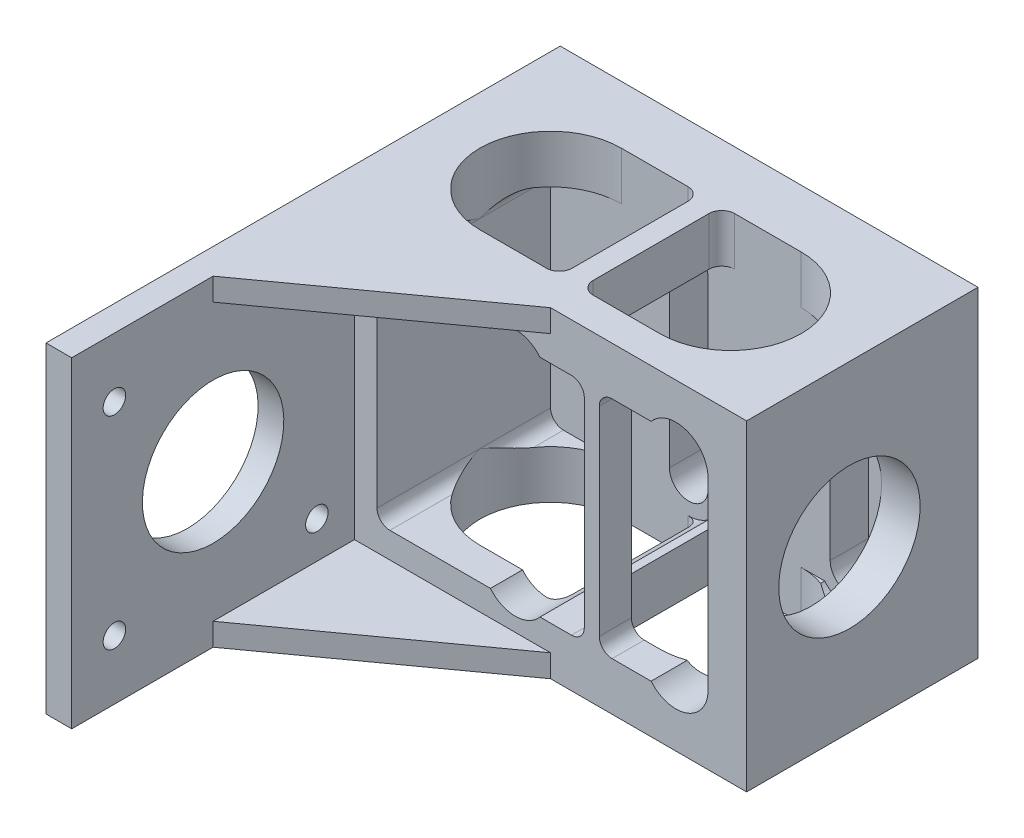
SolidWorks part; units mm, degrees
ref_plane "Ebene vorne" through (0, 0, 0) normal (0, 0, 1) x (1, 0, 0)
ref_plane "Ebene oben" through (0, 0, 0) normal (0, 1, 0) x (1, 0, 0)
ref_plane "Ebene rechts" through (0, 0, 0) normal (1, 0, 0) x (0, 0, -1)
sketch "Skizze1" plane through (0, 0, 0) normal (0, 0, 1) x (1, 0, 0)
  line L1 (-32.5, 25) -> (32.5, 25)
  line L2 (-32.5, 25) -> (-32.5, -25)
  line L3 (-32.5, -25) -> (32.5, -25)
  line L4 (32.5, 25) -> (32.5, -25)
  line L5 (-32.5, 25) -> (32.5, -25) construction
  line L6 (-32.5, -25) -> (32.5, 25) construction
  point P0 (0, 0)
  dimension "D1" = 50
  dimension "D2" = 65
extrude "Aufsatz-Linear austragen1" add sketch "Skizze1" along normal blind 36
sketch "Skizze2" plane through (-32.5, 0, 0) normal (-1, 0, 0) x (0, 0, 1)
  line L0 (36, 25) -> (0, 25) construction
  line L1 (0, 25) -> (80, 25)
  line L2 (0, 25) -> (0, -25)
  line L3 (0, -25) -> (80, -25)
  line L4 (80, 25) -> (80, -25)
  dimension "D1" = 80
extrude "Aufsatz-Linear austragen2" add sketch "Skizze2" against normal blind 4
sketch "Skizze3" plane through (-32.5, 0, 0) normal (-1, 0, 0) x (0, 0, 1)
  line L0 (55, 0) -> (-55, 0) construction
  line L1 (0, -55) -> (0, 55) construction
  circle A0 centre (58, 0) radius 11
  circle A1 centre (73.3603, 15.75) radius 1.75
  circle A2 centre (73.3603, -15.75) radius 1.75
  circle A3 centre (41.8603, -15.75) radius 1.75
  circle A4 centre (41.8603, 15.75) radius 1.75
  dimension "D1" = 22
  dimension "D3" = 3.5
  dimension "D4" = 3.5
  dimension "D5" = 3.5
  dimension "D6" = 3.5
  dimension "D7" = 31.5
  dimension "D8" = 31.5
  dimension "D2" = 58
  dimension "D9" = 22
  dimension "D10" = 22
extrude "Schnitt-Linear austragen1" cut sketch "Skizze3" against normal blind 4
sketch "Skizze4" plane through (0, 25, 0) normal (0, 1, 0) x (1, 0, 0)
  line L0 (-28.5, -58) -> (2, -36)
  line L1 (-28.5, -80) -> (-28.5, -36) construction
  line L2 (32.5, -36) -> (-28.5, -36) construction
  line L3 (2, -36) -> (-28.5, -36)
  line L4 (-28.5, -36) -> (-28.5, -58)
extrude "Aufsatz-Linear austragen3" add sketch "Skizze4" against normal blind 3.5
sketch "Skizze5" plane through (0, -25, 0) normal (0, -1, 0) x (1, 0, 0)
  line L0 (-28.5, 58) -> (2, 36)
  line L1 (-28.5, 36) -> (-28.5, 80) construction
  line L2 (-28.5, 36) -> (32.5, 36) construction
  line L3 (2, 36) -> (-28.5, 36)
  line L4 (-28.5, 36) -> (-28.5, 58)
extrude "Aufsatz-Linear austragen4" add sketch "Skizze5" against normal blind 3.5
sketch "Skizze6" plane through (0, 0, 36) normal (0, 0, 1) x (1, 0, 0)
  line L1 (-23, 17.5) -> (5.248, 17.5)
  line L2 (-25, 15.5) -> (-25, -15.5)
  line L3 (-23, -17.5) -> (5.248, -17.5)
  line L4 (25, 15.5) -> (25, -15.5)
  line L5 (-25, 17.5) -> (25, -17.5) construction
  line L6 (-25, -17.5) -> (25, 17.5) construction
  line L7 (35.75, 0) -> (-35.75, 0) construction
  line L9 (9.5746, 15.5) -> (9.5746, -15.5)
  line L11 (7.248, 15.5) -> (7.248, -15.5)
  line L12 (9.5746, 17.5) -> (7.248, -17.5) construction
  line L13 (9.5746, -17.5) -> (7.248, 17.5) construction
  line L14 (11.5746, 17.5) -> (23, 17.5)
  line L15 (11.5746, -17.5) -> (23, -17.5)
  arc A0 (23, 17.5) -> (25, 15.5) centre (23, 15.5) cw
  arc A1 (23, -17.5) -> (25, -15.5) centre (23, -15.5) ccw
  arc A2 (-23, -17.5) -> (-25, -15.5) centre (-23, -15.5) cw
  arc A3 (-23, 17.5) -> (-25, 15.5) centre (-23, 15.5) ccw
  arc A4 (11.5746, 17.5) -> (9.5746, 15.5) centre (11.5746, 15.5) ccw
  arc A5 (9.5746, -15.5) -> (11.5746, -17.5) centre (11.5746, -15.5) ccw
  arc A6 (5.248, -17.5) -> (7.248, -15.5) centre (5.248, -15.5) ccw
  arc A7 (5.248, 17.5) -> (7.248, 15.5) centre (5.248, 15.5) cw
  point P0 (0, 0)
  point P18 (8.4113, 0)
  dimension "D3" = 2
  dimension "D4" = 2
  dimension "D5" = 2
  dimension "D1" = 35
  dimension "D2" = 50
extrude "Schnitt-Linear austragen2" cut sketch "Skizze6" against normal blind 27
sketch "Skizze7" plane through (32.5, 0, 0) normal (1, 0, 0) x (0, 0, -1)
  line L0 (35.75, 0) -> (-35.75, 0) construction
  line L1 (0, 27.5) -> (0, -27.5) construction
  circle A0 centre (-20, 0) radius 11
  dimension "D1" = 22
  dimension "D2" = 20
extrude "Schnitt-Linear austragen3" cut sketch "Skizze7" against normal blind 54
sketch "Skizze8" plane through (0, 25, 0) normal (0, 1, 0) x (1, 0, 0)
  line L0 (0, -27.5) -> (0, 27.5) construction
  line L2 (-14, -20) -> (14, -20) construction
  line L3 (-14, -9) -> (-3.639, -9)
  line L4 (-14, -31) -> (-3.639, -31)
  line L5 (-27.5, 0) -> (27.5, 0) construction
  line L6 (3.639, -9) -> (14, -9)
  line L8 (-1.639, -29) -> (-1.639, -11)
  line L10 (1.639, -29) -> (1.639, -11)
  line L11 (-1.639, -31) -> (1.639, -9) construction
  line L12 (-1.639, -9) -> (1.639, -31) construction
  line L13 (3.639, -31) -> (14, -31)
  arc A1 (-14, -9) -> (-14, -31) centre (-14, -20) ccw
  arc A2 (14, -31) -> (14, -9) centre (14, -20) ccw
  arc A3 (3.639, -9) -> (1.639, -11) centre (3.639, -11) ccw
  arc A4 (3.639, -31) -> (1.639, -29) centre (3.639, -29) cw
  arc A5 (-3.639, -31) -> (-1.639, -29) centre (-3.639, -29) ccw
  arc A6 (-1.639, -11) -> (-3.639, -9) centre (-3.639, -11) ccw
  point P4 (0, -20)
  point P8 (0, -20)
  dimension "D1" = 28
  dimension "D4" = 2
  dimension "D2" = 9
  dimension "D3" = 22
extrude "Schnitt-Linear austragen4" cut sketch "Skizze8" against normal blind 54
sketch "Skizze9" plane through (0, 0, 9) normal (0, 0, 1) x (1, 0, 0)
  line L0 (35.75, 0) -> (-35.75, 0) construction
  line L3 (-32.5, -25) -> (-32.5, 25) construction
  line L8 (-3.5, 14.3191) -> (-3.5, -14.3191) construction
  line L9 (-0.5, 14.3191) -> (-0.5, -14.3191)
  line L10 (-6.5, 14.3191) -> (-6.5, -14.3191)
  line L11 (21.5, 14.3191) -> (21.5, -14.3191) construction
  line L12 (24.5, 14.3191) -> (24.5, -14.3191)
  line L13 (18.5, 14.3191) -> (18.5, -14.3191)
  arc A4 (-0.5, 14.3191) -> (-6.5, 14.3191) centre (-3.5, 14.3191) ccw
  arc A5 (-6.5, -14.3191) -> (-0.5, -14.3191) centre (-3.5, -14.3191) ccw
  arc A6 (24.5, 14.3191) -> (18.5, 14.3191) centre (21.5, 14.3191) ccw
  arc A7 (18.5, -14.3191) -> (24.5, -14.3191) centre (21.5, -14.3191) ccw
  point P14 (-3.5, 0)
  point P23 (21.5, 0)
  dimension "D1" = 6
  dimension "D2" = 6
  dimension "D3" = 25
  dimension "D4" = 29
extrude "Schnitt-Linear austragen10" cut sketch "Skizze9" against normal blind 37
sketch "Skizze14" plane through (0, 0, 9) normal (0, 0, 1) x (1, 0, 0)
  line L0 (-3.5, 14.3191) -> (-3.5, -14.3191) construction
  line L1 (1.5, 14.3191) -> (1.5, -14.3191)
  line L2 (-8.5, 14.3191) -> (-8.5, -14.3191)
  line L3 (21.5, 14.3191) -> (21.5, -14.3191) construction
  line L4 (26.5, 14.3191) -> (26.5, -14.3191)
  line L5 (16.5, 14.3191) -> (16.5, -14.3191)
  line L6 (-6.5, 14.3191) -> (-6.5, -14.3191) construction
  line L7 (24.5, -14.3191) -> (24.5, 14.3191) construction
  arc A0 (1.5, 14.3191) -> (-8.5, 14.3191) centre (-3.5, 14.3191) ccw
  arc A1 (-8.5, -14.3191) -> (1.5, -14.3191) centre (-3.5, -14.3191) ccw
  arc A2 (26.5, 14.3191) -> (16.5, 14.3191) centre (21.5, 14.3191) ccw
  arc A3 (16.5, -14.3191) -> (26.5, -14.3191) centre (21.5, -14.3191) ccw
  point P3 (-3.5, 0)
  point P8 (21.5, 0)
  dimension "D1" = 2
  dimension "D2" = 2
extrude "Schnitt-Linear austragen11" cut sketch "Skizze14" along normal blind 37
